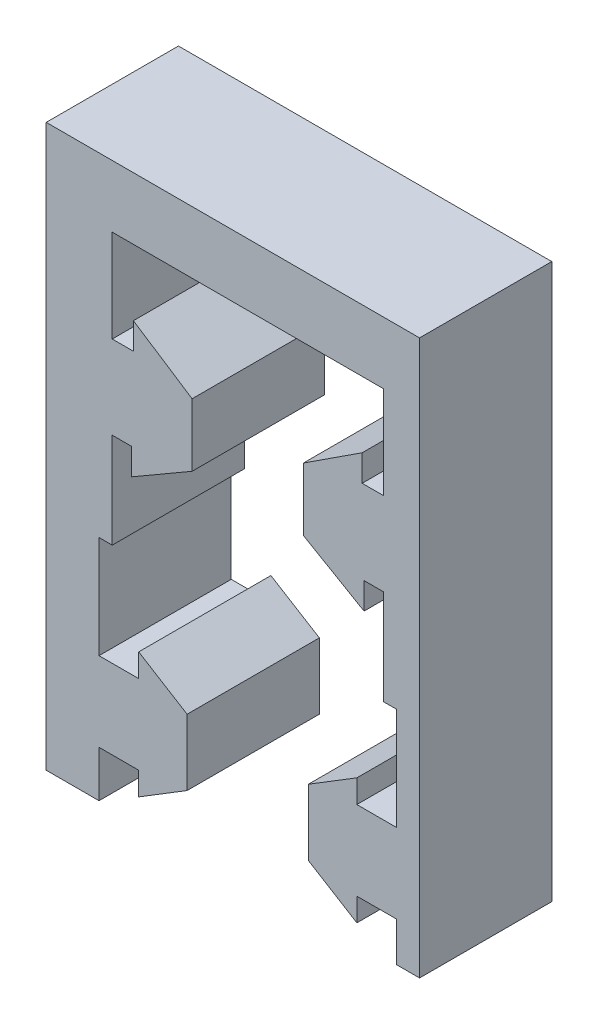
SolidWorks part; units mm, degrees
ref_plane "Ön Düzlem" through (0, 0, 0) normal (0, 0, 1) x (1, 0, 0)
ref_plane "Üst Düzlem" through (0, 0, 0) normal (0, 1, 0) x (1, 0, 0)
ref_plane "Sağ Düzlem" through (0, 0, 0) normal (1, 0, 0) x (0, 0, -1)
sketch "Çizim1" plane through (0, 0, 0) normal (0, 0, 1) x (1, 0, 0)
  line L0 (0, 0.5) -> (0, 7.7)
  line L1 (0, 21) -> (-20.5, 21)
  line L2 (-20.5, 21) -> (-20.5, 14)
  line L5 (-21.5, -7.2412) -> (-18.5, -7.2412)
  line L6 (-18.5, -7.2412) -> (-18.5, -5.4912)
  line L7 (-18.5, -13.2412) -> (-18.5, -14.9912)
  line L8 (-18.5, -14.9912) -> (-14.8356, -12.7412)
  line L9 (-14.8356, -12.7412) -> (-14.8356, -7.7412)
  line L10 (-14.8356, -7.7412) -> (-18.5, -5.4912)
  line L11 (-18.5, -13.2412) -> (-21.5, -13.2412)
  line L12 (1, 0.5) -> (1, -7.2412)
  line L14 (-25.4929, -16.7412) -> (-25.4929, 25.6949)
  line L15 (-25.4929, 25.6949) -> (2.7416, 25.6949)
  line L18 (-10.25, 21) -> (-10.25, -20.2034) construction
  line L19 (-20.5, 0.5) -> (-21.5, 0.5)
  line L20 (1, -16.2305) -> (2.7416, -16.2305)
  line L21 (2.7416, -16.2305) -> (2.7416, 25.6949)
  line L22 (-2, -13.2412) -> (1, -13.2412)
  line L23 (-5.6644, -7.7412) -> (-2, -5.4912)
  line L24 (-5.6644, -12.7412) -> (-5.6644, -7.7412)
  line L25 (-2, -14.9912) -> (-5.6644, -12.7412)
  line L26 (-20.5, 7.7) -> (-19.0444, 7.7)
  line L27 (-19.0444, 7.7) -> (-19.0444, 5.7)
  line L28 (-19.0444, 5.7) -> (-14.4589, 8.3575)
  line L29 (-14.4589, 8.3575) -> (-14.4589, 13.1075)
  line L30 (-14.4589, 13.1075) -> (-18.9, 16)
  line L31 (-18.9, 16) -> (-18.9, 14)
  line L32 (-18.9, 14) -> (-20.5, 14)
  line L33 (-1.6, 14) -> (0, 14)
  line L34 (-1.6, 16) -> (-1.6, 14)
  line L35 (-6.0411, 13.1075) -> (-1.6, 16)
  line L36 (-6.0411, 8.3575) -> (-6.0411, 13.1075)
  line L37 (-1.4556, 5.7) -> (-6.0411, 8.3575)
  line L38 (-1.4556, 7.7) -> (-1.4556, 5.7)
  line L39 (0, 7.7) -> (-1.4556, 7.7)
  line L40 (-20.5, 0.5) -> (-21.5, 0.5)
  line L41 (-21.5, 0.5) -> (-21.5, -7.2412)
  line L42 (-2, -13.2412) -> (-2, -14.9912)
  line L43 (1, 0.5) -> (0, 0.5)
  line L44 (-21.5, 0.5) -> (-20.5, 0.5)
  line L45 (-2, -7.2412) -> (-2, -5.4912)
  line L46 (1, -7.2412) -> (-2, -7.2412)
  line L47 (-20.5, 7.7) -> (-20.5, 0.5)
  line L48 (0, 14) -> (0, 21)
  line L49 (1, -13.2412) -> (1, -16.2305)
  line L50 (-21.5, -13.2412) -> (-21.5, -16.7412)
  line L51 (-25.4929, -16.7412) -> (-21.5, -16.7412)
  dimension "D3" = 20.5
  dimension "D4" = 41.2034
  dimension "D5" = 1
  dimension "D6" = 3
  dimension "D7" = 3
  dimension "D8" = 6
  dimension "D9" = 1.75
  dimension "D10" = 1.75
  dimension "D11" = 5
  dimension "D12" = 4.3
  dimension "D13" = 4.3
  dimension "D14" = 9.1713
  dimension "D15" = 6.3
  dimension "D16" = 7
  dimension "D18" = 1.6
  dimension "D19" = 2
  dimension "D20" = 2
  dimension "D21" = 5.3
  dimension "D22" = 5.3
  dimension "D23" = 4.75
  dimension "D24" = 1.6
  dimension "D25" = 5.3
  dimension "D26" = 4.75
  dimension "D27" = 8.4177
extrude "Yükseklik-Ekstrüzyon2" add sketch "Çizim1" along normal blind 10 contours L14 L51 L50 L11 L7 L8 L9 L10 L6 L5 L41 L19 L47 L26 L27 L28 L29 L30 L31 L32 L2 L1 L48 L33 L34 L35 L36 L37 L38 L39 L0 L43 L12 L46 L45 L23 L24 L25 L42 L22 L49 L20 L21 L15
